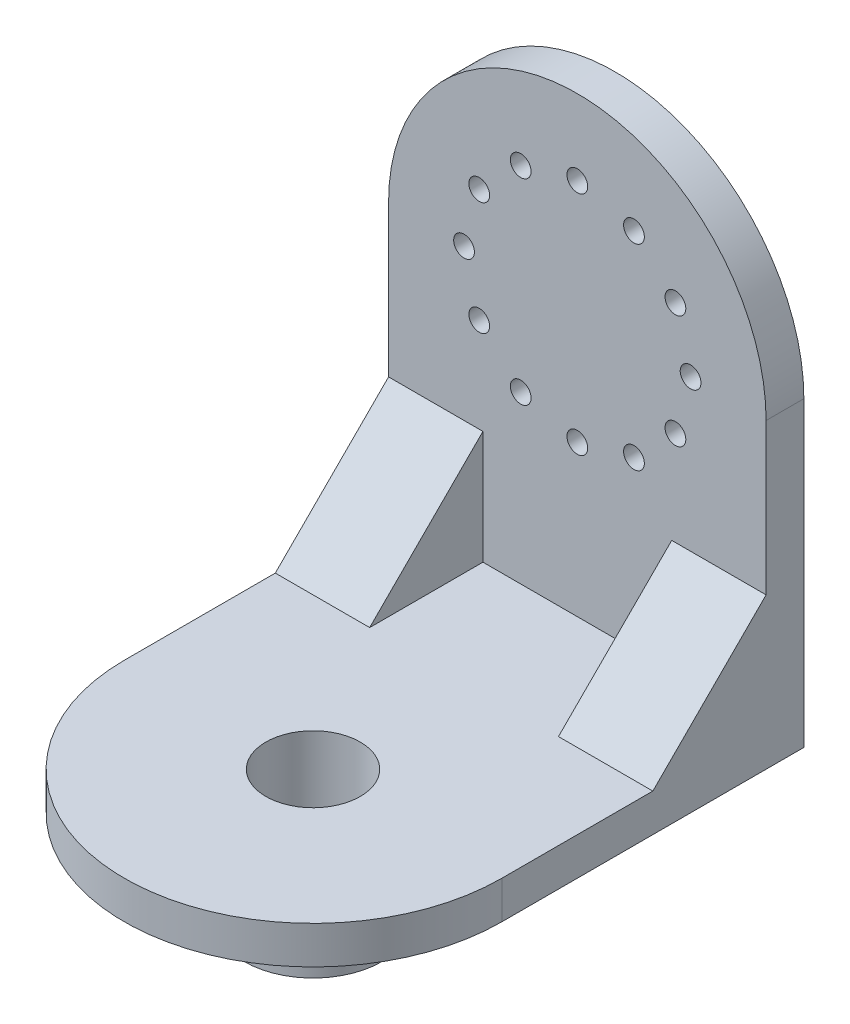
SolidWorks part; units mm, degrees
ref_plane "前视基准面" through (0, 0, 0) normal (0, 0, 1) x (1, 0, 0)
ref_plane "上视基准面" through (0, 0, 0) normal (0, 1, 0) x (1, 0, 0)
ref_plane "右视基准面" through (0, 0, 0) normal (1, 0, 0) x (0, 0, -1)
other "Configuration Table"
sketch "草图1" plane through (0, 0, 0) normal (0, 0, 1) x (1, 0, 0)
  line L0 (-50, 0) -> (-50, -80)
  line L1 (-50, -80) -> (50, -80)
  line L2 (50, -80) -> (50, 0)
  arc A0 (50, 0) -> (-50, 0) centre (0, 0) ccw
  dimension "D1" = 100
  dimension "D2" = 80
extrude "凸台-拉伸1" add sketch "草图1" along normal blind 10
sketch "草图2" plane through (0, -80, 0) normal (0, -1, 0) x (1, 0, 0)
  line L0 (50, 10) -> (50, 80)
  line L1 (-50, 80) -> (-50, 10)
  line L2 (50, 10) -> (-50, 10)
  arc A0 (50, 80) -> (-50, 80) centre (0, 80) ccw
  dimension "D1" = 100
  dimension "D2" = 80
extrude "凸台-拉伸2" add sketch "草图2" against normal blind 10
sketch "草图3" plane through (-50, 0, 0) normal (-1, 0, 0) x (0, 0, 1)
  line L0 (10, -40) -> (40, -70)
  line L1 (10, 0) -> (10, -70) construction
  line L2 (80, -70) -> (10, -70) construction
  line L3 (40, -70) -> (10, -70)
  line L4 (10, -70) -> (10, -40)
  dimension "D1" = 30
  dimension "D2" = 30
extrude "凸台-拉伸3" add sketch "草图3" against normal blind 25
sketch "草图4" plane through (50, 0, 0) normal (1, 0, 0) x (0, 0, -1)
  line L3 (-10, -70) -> (-10, -40)
  line L4 (-10, -40) -> (-40, -70)
  line L5 (-40, -70) -> (-10, -70)
  line L6 (-10, -70) -> (-10, -40)
  line L7 (-10, -40) -> (-40, -70)
  line L8 (-40, -70) -> (-10, -70)
  dimension "D1" = 0
extrude "凸台-拉伸4" add sketch "草图4" against normal blind 25
sketch "草图5" plane through (0, 0, 10) normal (0, 0, 1) x (1, 0, 0)
  line L0 (0, 0) -> (50000, 0) construction
  line L1 (0, 0) -> (0, -50000) construction
  line L2 (0, 0) -> (43301.2702, 25000) construction
  line L3 (0, 0) -> (25000, 43301.2702) construction
  circle A0 centre (0, 0) radius 30 construction
  circle A1 centre (0, 30) radius 2.75
  circle A2 centre (30, 0) radius 2.75
  circle A3 centre (0, -30) radius 2.75
  circle A4 centre (-30, 0) radius 2.75
  circle A5 centre (15, 25.9808) radius 2.75
  circle A6 centre (25.9808, 15) radius 2.75
  circle A7 centre (15, -25.9808) radius 2.75
  circle A8 centre (25.9808, -15) radius 2.75
  circle A9 centre (-15, 25.9808) radius 2.75
  circle A10 centre (-25.9808, 15) radius 2.75
  circle A11 centre (-25.9808, -15) radius 2.75
  circle A12 centre (-15, -25.9808) radius 2.75
  point P23 (0, 0)
  point P24 (15.5464, 26.9272)
  dimension "D1" = 60
  dimension "D2" = 5.5
  dimension "D5" = 5.5
  dimension "D6" = 5.5
  dimension "D3" = 30
  dimension "D4" = 30
extrude "切除-拉伸1" cut sketch "草图5" against normal blind 25
sketch "草图6" plane through (0, -80, 0) normal (0, -1, 0) x (1, 0, 0)
  circle A0 centre (0, 80) radius 18.25
  circle A1 centre (0, 80) radius 12.5
  dimension "D1" = 36.5
  dimension "D2" = 25
extrude "凸台-拉伸5" add sketch "草图6" along normal blind 25
sketch "草图7" plane through (0, -80, 0) normal (0, -1, 0) x (1, 0, 0)
  circle A1 centre (0, 80) radius 12.5
  circle A2 centre (0, 80) radius 12.5
  dimension "D1" = 0
extrude "切除-拉伸2" cut sketch "草图7" against normal blind 10
